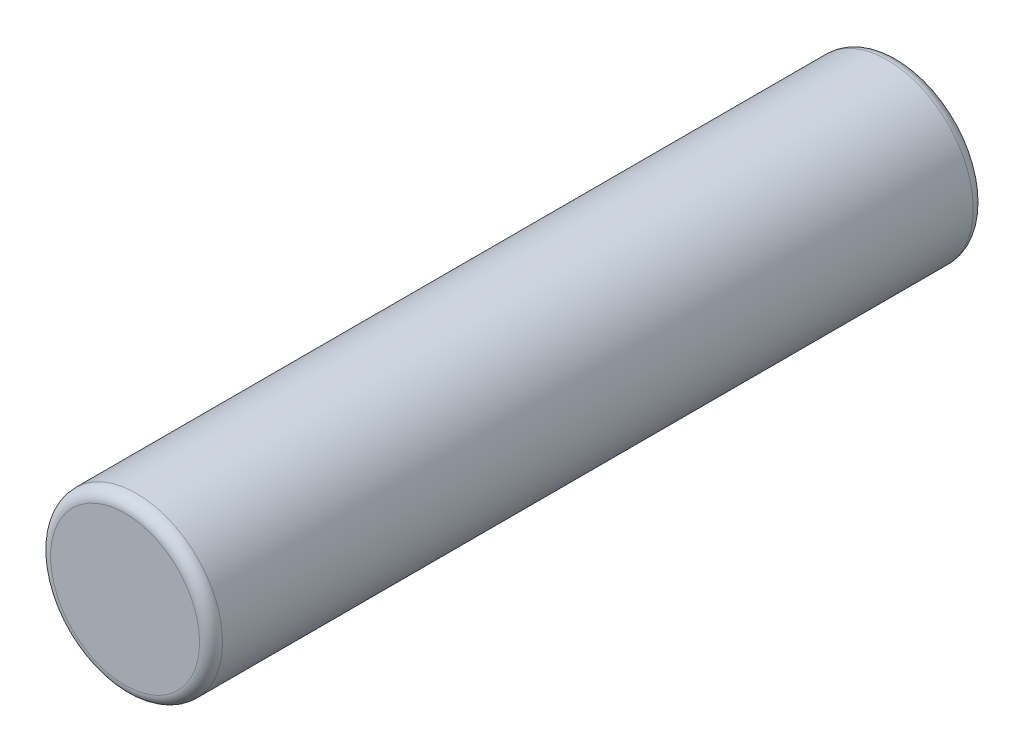
SolidWorks part; units mm, degrees
ref_plane "Front Plane" through (0, 0, 0) normal (0, 0, 1) x (1, 0, 0)
ref_plane "Top Plane" through (0, 0, 0) normal (0, 1, 0) x (1, 0, 0)
ref_plane "Right Plane" through (0, 0, 0) normal (1, 0, 0) x (0, 0, -1)
sketch "Sketch1" plane through (0, 0, 0) normal (0, 0, 1) x (1, 0, 0)
  circle A0 centre (0, 0) radius 1.5
extrude "Boss-Extrude1" add sketch "Sketch1" along normal blind 13.5
fillet "Fillet1" radius 0.2 2 edges at (1.5, 0, 13.5) (1.5, 0, 0)
